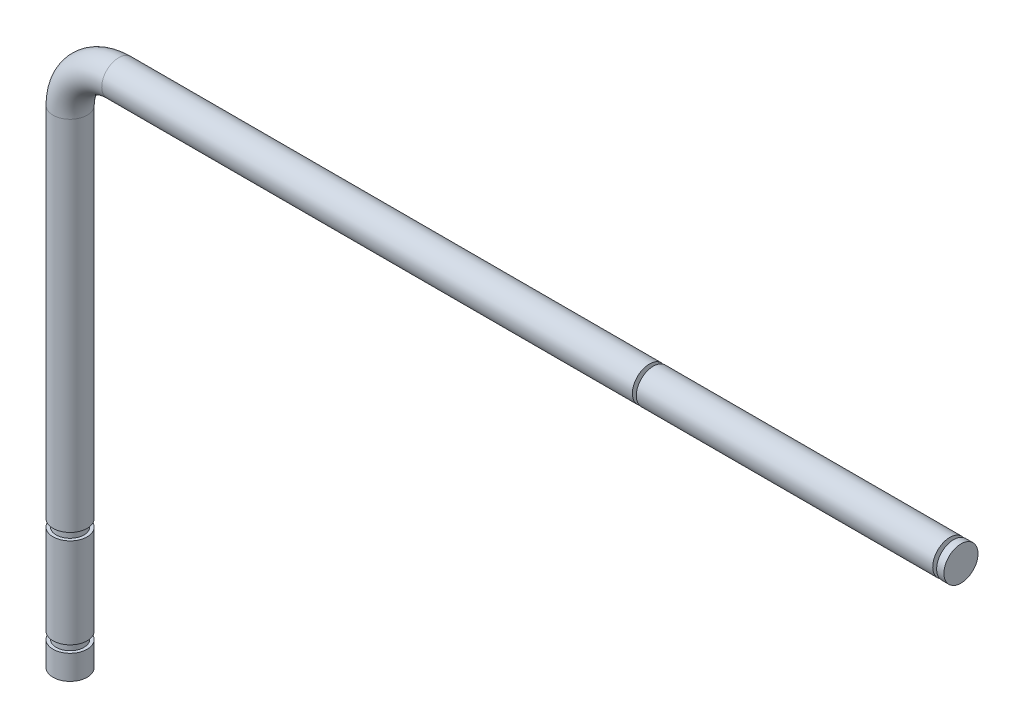
SolidWorks part; units mm, degrees
material "Stal węglowa"
ref_plane "Płaszczyzna przednia" through (0, 0, 0) normal (0, 0, 1) x (1, 0, 0)
ref_plane "Płaszczyzna górna" through (0, 0, 0) normal (0, 1, 0) x (1, 0, 0)
ref_plane "Płaszczyzna prawa" through (0, 0, 0) normal (1, 0, 0) x (0, 0, -1)
sketch "Szkic1" plane through (0, 0, 0) normal (0, 0, 1) x (1, 0, 0)
  line L0 (10, 0) -> (183, 0)
  line L1 (0, -10) -> (0, -110)
  arc A0 (10, 0) -> (0, -10) centre (10, -10) ccw
  point P6 (0, 0)
  dimension "D3" = 10
  dimension "D1" = 183
  dimension "D2" = 110
sweep "Wyciągnięcie po ścieżce1" add path "Szkic1" circular profile diameter 7 parameters "D3"=7
ref_plane "Płaszczyzna2" through (0, -105, 0) normal (0, -1, 0) x (-1, 0, 0)
sketch "Szkic26" plane through (0, -105, 0) normal (0, -1, 0) x (-1, 0, 0)
  circle A0 centre (0, 0) radius 2.85
  circle A1 centre (0, 0) radius 4
  dimension "D1" = 5.7
  dimension "D2" = 8
extrude "Wytnij-wyciągnięcie1" cut sketch "Szkic26" against normal blind 1.5
ref_plane "Płaszczyzna8" through (0, -85, 0) normal (0, -1, 0) x (-1, 0, 0)
sketch "Szkic36" plane through (0, -85, 0) normal (0, -1, 0) x (-1, 0, 0)
  circle A0 centre (0, 0) radius 2.85
  circle A1 centre (0, 0) radius 4
  dimension "D1" = 5.7
  dimension "D2" = 8
extrude "Wytnij-wyciągnięcie3" cut sketch "Szkic36" against normal blind 1.5
ref_plane "Płaszczyzna10" through (181.5, 0, 0) normal (1, 0, 0) x (0, 0, -1)
sketch "Szkic46" plane through (181.5, 0, 0) normal (1, 0, 0) x (0, 0, -1)
  circle A0 centre (0, 0) radius 4
  circle A1 centre (0, 0) radius 1.6
  dimension "D1" = 3.2
  dimension "D2" = 8
extrude "Wytnij-wyciągnięcie4" cut sketch "Szkic46" against normal blind 0.8
ref_plane "Płaszczyzna11" through (119, 0, 0) normal (1, 0, 0) x (0, 0, -1)
sketch "Szkic53" plane through (119, 0, 0) normal (1, 0, 0) x (0, 0, -1)
  circle A0 centre (0, 0) radius 4
  circle A1 centre (0, 0) radius 1.6
  dimension "D1" = 8
  dimension "D2" = 3.2
extrude "Wytnij-wyciągnięcie5" cut sketch "Szkic53" along normal blind 0.8
